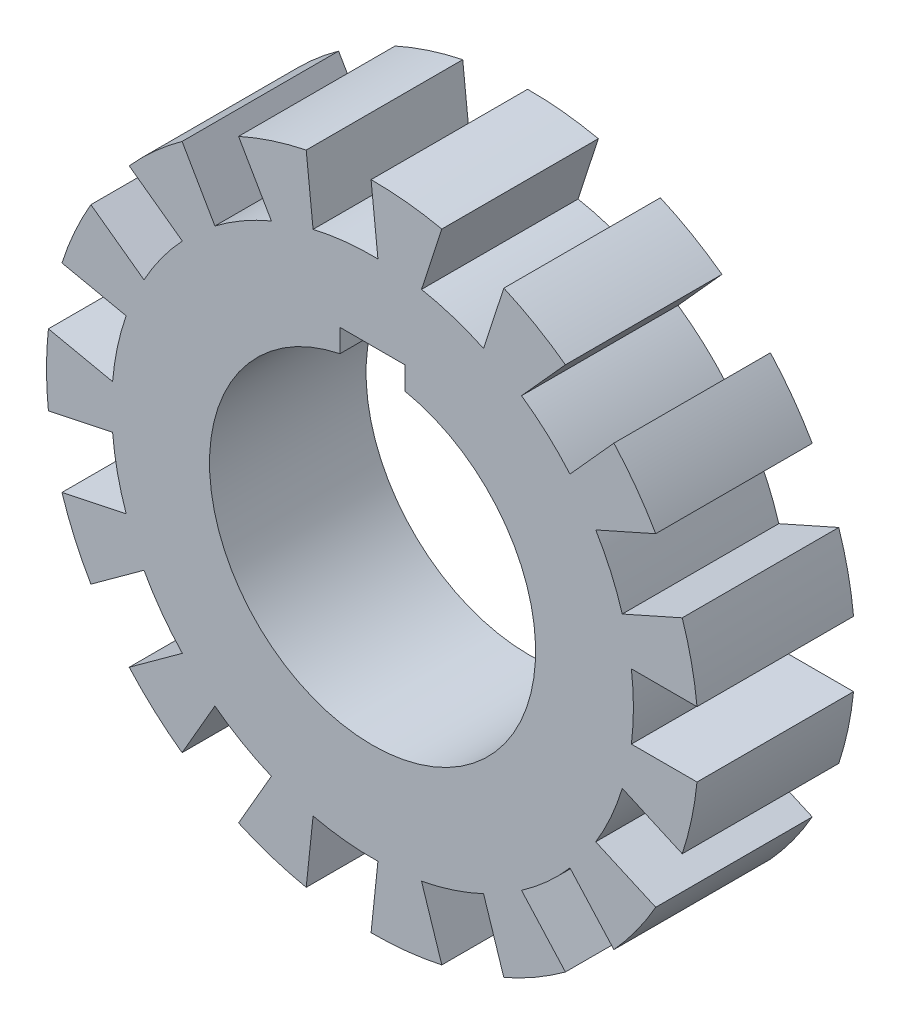
SolidWorks part; units mm, degrees
ref_plane "Front Plane" through (0, 0, 0) normal (0, 0, 1) x (1, 0, 0)
ref_plane "Top Plane" through (0, 0, 0) normal (0, 1, 0) x (1, 0, 0)
ref_plane "Right Plane" through (0, 0, 0) normal (1, 0, 0) x (0, 0, -1)
sketch "Sketch1" plane through (0, 0, 0) normal (0, 0, 1) x (1, 0, 0)
  line L1 (-5, 28) -> (5, 28)
  line L4 (5, 28) -> (5, 24.4949)
  line L5 (-5, 28) -> (-5, 24.4949)
  line L7 (39.6863, 5) -> (49.7494, 5)
  line L8 (38.2889, -11.5741) -> (47.482, -15.6672)
  line L9 (30.271, -26.147) -> (37.0046, -33.6253)
  line L10 (17.019, -36.1988) -> (20.1287, -45.7694)
  line L11 (0.8243, -39.9915) -> (-0.2276, -49.9995)
  line L12 (-15.513, -36.8693) -> (-20.5446, -45.5842)
  line L13 (-29.1679, -27.3721) -> (-37.3092, -33.287)
  line L14 (-37.7795, -13.142) -> (-47.6227, -15.2342)
  line L15 (-39.8586, 3.3605) -> (-49.7018, 5.4527)
  line L16 (-35.0458, 19.2819) -> (-43.187, 25.1969)
  line L17 (-24.1733, 31.8693) -> (-29.2048, 40.5842)
  line L18 (-9.121, 38.9462) -> (-10.1728, 48.9542)
  line L19 (7.5084, 39.289) -> (10.6181, 48.8595)
  line L20 (22.8396, 32.8383) -> (29.5731, 40.3166)
  line L21 (34.2215, 20.7096) -> (43.4146, 24.8026)
  line L22 (39.6863, -5) -> (49.7494, -5)
  line L23 (34.2215, -20.7096) -> (43.4146, -24.8026)
  line L24 (22.8396, -32.8383) -> (29.5731, -40.3166)
  line L25 (7.5084, -39.289) -> (10.6181, -48.8595)
  line L26 (-9.121, -38.9462) -> (-10.1728, -48.9542)
  line L27 (-24.1733, -31.8693) -> (-29.2048, -40.5842)
  line L28 (-35.0458, -19.2819) -> (-43.187, -25.1969)
  line L29 (-39.8586, -3.3605) -> (-49.7018, -5.4527)
  line L30 (-37.7795, 13.142) -> (-47.6227, 15.2342)
  line L31 (-29.1679, 27.3721) -> (-37.3092, 33.287)
  line L32 (-15.513, 36.8693) -> (-20.5446, 45.5842)
  line L33 (0.8243, 39.9915) -> (-0.2276, 49.9995)
  line L34 (17.019, 36.1988) -> (20.1287, 45.7694)
  line L35 (30.271, 26.147) -> (37.0046, 33.6253)
  line L36 (38.2889, 11.5741) -> (47.482, 15.6672)
  arc A0 (43.4146, 24.8026) -> (37.0046, 33.6253) centre (0, 0) ccw
  arc A1 (-39.8586, -3.3605) -> (-37.7795, -13.142) centre (0, 0) ccw
  arc A2 (-5, 24.4949) -> (5, 24.4949) centre (0, 0) ccw
  arc A3 (29.5731, 40.3166) -> (20.1287, 45.7694) centre (0, 0) ccw
  arc A4 (10.6181, 48.8595) -> (-0.2276, 49.9995) centre (0, 0) ccw
  arc A5 (-10.1728, 48.9542) -> (-20.5446, 45.5842) centre (0, 0) ccw
  arc A6 (-29.2048, 40.5842) -> (-37.3092, 33.287) centre (0, 0) ccw
  arc A7 (-43.187, 25.1969) -> (-47.6227, 15.2342) centre (0, 0) ccw
  arc A8 (-49.7018, 5.4527) -> (-49.7018, -5.4527) centre (0, 0) ccw
  arc A9 (-47.6227, -15.2342) -> (-43.187, -25.1969) centre (0, 0) ccw
  arc A10 (-37.3092, -33.287) -> (-29.2048, -40.5842) centre (0, 0) ccw
  arc A11 (-20.5446, -45.5842) -> (-10.1728, -48.9542) centre (0, 0) ccw
  arc A12 (49.7494, 5) -> (47.482, 15.6672) centre (0, 0) ccw
  arc A13 (37.0046, -33.6253) -> (43.4146, -24.8026) centre (0, 0) ccw
  arc A14 (47.482, -15.6672) -> (49.7494, -5) centre (0, 0) ccw
  arc A15 (20.1287, -45.7694) -> (29.5731, -40.3166) centre (0, 0) ccw
  arc A16 (-0.2276, -49.9995) -> (10.6181, -48.8595) centre (0, 0) ccw
  arc A17 (-37.7795, 13.142) -> (-39.8586, 3.3605) centre (0, 0) ccw
  arc A18 (-29.1679, 27.3721) -> (-35.0458, 19.2819) centre (0, 0) ccw
  arc A19 (-15.513, 36.8693) -> (-24.1733, 31.8693) centre (0, 0) ccw
  arc A20 (0.8243, 39.9915) -> (-9.121, 38.9462) centre (0, 0) ccw
  arc A21 (17.019, 36.1988) -> (7.5084, 39.289) centre (0, 0) ccw
  arc A22 (30.271, 26.147) -> (22.8396, 32.8383) centre (0, 0) ccw
  arc A23 (38.2889, 11.5741) -> (34.2215, 20.7096) centre (0, 0) ccw
  arc A24 (39.6863, -5) -> (39.6863, 5) centre (0, 0) ccw
  arc A25 (34.2215, -20.7096) -> (38.2889, -11.5741) centre (0, 0) ccw
  arc A26 (22.8396, -32.8383) -> (30.271, -26.147) centre (0, 0) ccw
  arc A27 (7.5084, -39.289) -> (17.019, -36.1988) centre (0, 0) ccw
  arc A28 (-9.121, -38.9462) -> (0.8243, -39.9915) centre (0, 0) ccw
  arc A29 (-24.1733, -31.8693) -> (-15.513, -36.8693) centre (0, 0) ccw
  arc A30 (-35.0458, -19.2819) -> (-29.1679, -27.3721) centre (0, 0) ccw
  point P12 (0, 28)
  point P46 (0, 0)
  point P77 (0, 0)
  dimension "D1" = 5
  dimension "D3" = 50
  dimension "D4" = 80
  dimension "D5" = 100
  dimension "D6" = 5
  dimension "D2" = 28
  dimension "D8" = 10
  dimension "D9" = 15
  dimension "D10" = 10
  dimension "D7" = 15
extrude "Boss-Extrude2" add sketch "Sketch1" along normal blind 24
